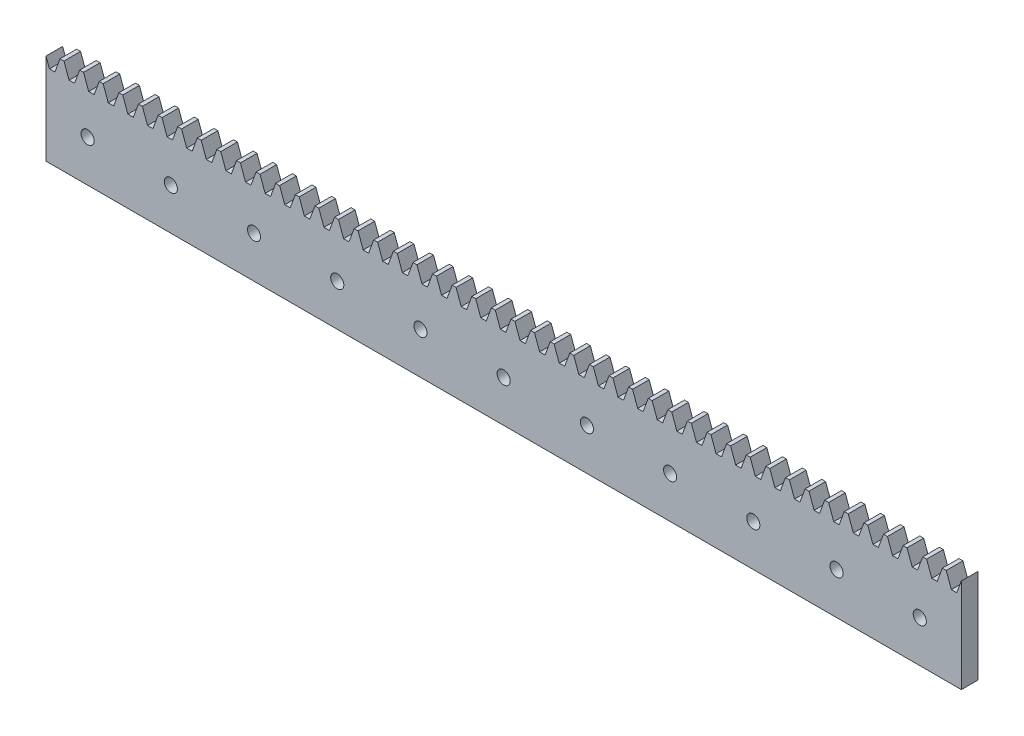
SolidWorks part; units mm, degrees
extrude "Blank" add sketch "BlankSke" against normal blind 4
sketch "BlankSke" plane through (0, 0, 0) normal (0, 0, 1) x (1, 0, 0)
  line L1 (0, 0) -> (660, 0)
  line L2 (0, 0) -> (0, 23)
  line L3 (0, 23) -> (660, 23)
  line L4 (660, 0) -> (660, 23)
  dimension "Length" = 660
  dimension "Blank_height" = 23
ref_plane "Plane1" through (0, 0, 0) normal (0, 0, 1) x (1, 0, 0)
ref_plane "Plane2" through (0, 0, 0) normal (0, 1, 0) x (1, 0, 0)
ref_plane "Plane3" through (0, 0, 0) normal (1, 0, 0) x (0, 0, -1)
other "Configuration Table"
sketch "HoldingSke" plane through (0, 0, 0) normal (0, 1, 0) x (1, 0, 0)
  line L0 (0, 0) -> (0.0928, 0.6602)
  line L1 (-15, 0) -> (100, 0) construction
  line L2 (0, 0) -> (-2.1039, 2.3779)
  line L3 (0, 0) -> (-11.863, 4.5341)
  line L4 (0, 0) -> (-6.8053, 5.3169)
  line L5 (0, 0) -> (-23.7986, -8.8762)
  line L6 (0, 0) -> (-10.5278, -7.1032)
  line L9 (-71.009, 38.7566) -> (549.1882, 264.4899)
  line L10 (-76.2, 3.8779) -> (-54.7, 3.8779)
  line L11 (0, 0) -> (-4, 0)
  line L12 (-76.2, 101.6) -> (-76.147, 101.6)
  line L13 (24.9733, 27.94) -> (52.9518, 28.4284)
  line L14 (24.9733, 27.94) -> (24.9743, 27.94)
  line L15 (24.9733, 27.94) -> (100.4006, 29.5858)
  circle A0 centre (0, 0) radius 19.05
  circle A1 centre (0, 0) radius 10.75
  circle A2 centre (0, 0) radius 12.7
  dimension "MPH" = 21.5
  dimension "Diameter" = 38.1
  dimension "Num_teeth" = 142
  dimension "Pitch" = 0.6667
  dimension "Show_teeth" = 998
  dimension "Thickness" = 12.7
  dimension "Ap" = 20
  dimension "Pitch_height" = 21.5
  dimension "Width" = 4
  dimension "Backlash" = 0.053
  dimension "Addendum_fac" = 1
  dimension "Dedendum_fac" = 1.25
  dimension "Clearance_fac" = 0.25
  dimension "Dedendum_add" = 0.001
  dimension "Length" = 660
  dimension "Module" = 1.5
sketch "TooCutSkeIll" plane through (0, 0, 0) normal (0, 0, 1) x (1, 0, 0)
  line L0 (-1.8687, 22.9605) -> (-0.7447, 19.8724)
  line L1 (-0.3914, 19.625) -> (0.3914, 19.625)
  line L2 (0.7447, 19.8724) -> (1.8687, 22.9605)
  line L3 (660, 23) -> (0, 23) construction
  line L4 (0, 0) -> (0, 64.897) construction
  line L5 (-13.208, 21.5) -> (12.954, 21.5) construction
  line L6 (0, 0) -> (660, 0) construction
  line L7 (1.3371, 21.5) -> (1.3371, 48.7463) construction
  line L8 (-1.3371, 21.5) -> (-1.3371, 48.7463) construction
  line L9 (1.9251, 23) -> (1.9251, 23.0254)
  line L10 (-1.9251, 23) -> (-1.9251, 23.0254)
  line L11 (-1.9251, 23.0254) -> (1.9251, 23.0254)
  arc A0 (0.3914, 19.625) -> (0.7447, 19.8724) centre (0.3914, 20.001) ccw
  arc A1 (-0.7447, 19.8724) -> (-0.3914, 19.625) centre (-0.3914, 20.001) ccw
  arc A2 (1.9251, 23) -> (1.8687, 22.9605) centre (1.9251, 22.94) ccw
  arc A3 (-1.8687, 22.9605) -> (-1.9251, 23) centre (-1.9251, 22.94) ccw
  dimension "Pitch_height" = 21.5
  dimension "Addendum_plus" = 1.5254
  dimension "Pressure_angle" = 20
  dimension "Gap_width" = 2.6742
  dimension "Dedendum" = 1.875
extrude "ToothCutIll" [suppressed] cut sketch "TooCutSkeIll" against normal through all
sketch "TooCutSkeSim" plane through (0, 0, 0) normal (0, 0, 1) x (1, 0, 0)
  line L0 (0.6547, 19.625) -> (-0.6547, 19.625)
  line L1 (1.8923, 23.0254) -> (0.6547, 19.625)
  line L2 (0, 17.4625) -> (0, 53.467) construction
  line L3 (1.8923, 23.0254) -> (-1.8923, 23.0254)
  line L6 (-1.8923, 23.0254) -> (-0.6547, 19.625)
  line L9 (-1.3371, 21.5) -> (1.3371, 21.5) construction
  line L10 (0, 0) -> (660, 0) construction
  line L11 (1.3371, 21.5) -> (1.3371, 53.467) construction
  line L12 (-1.3371, 21.5) -> (-1.3371, 53.467) construction
  dimension "Pitch_height" = 21.5
  dimension "Addendum_plus" = 1.5254
  dimension "Pressure_angle" = 20
  dimension "Gap_width" = 2.6742
  dimension "Dedendum" = 1.875
extrude "ToothCutSim" cut sketch "TooCutSkeSim" against normal through all
pattern_linear "TeethCuts" count 141 spacing 4.7124 along (1, 0, 0) of "ToothCutIll", "ToothCutSim"
sketch "草图2" plane through (0, 0, 0) normal (0, 0, 1) x (1, 0, 0)
  line L0 (660, 0) -> (660, 19.625) construction
  line L2 (0, 0) -> (660, 0) construction
  circle A0 centre (650, 10) radius 1.575
  circle A1 centre (630, 10) radius 1.575
  circle A2 centre (610, 10) radius 1.575
  circle A3 centre (590, 10) radius 1.575
  circle A4 centre (570, 10) radius 1.575
  circle A5 centre (550, 10) radius 1.575
  circle A6 centre (530, 10) radius 1.575
  circle A7 centre (510, 10) radius 1.575
  circle A8 centre (490, 10) radius 1.575
  circle A9 centre (470, 10) radius 1.575
  circle A10 centre (450, 10) radius 1.575
  circle A11 centre (430, 10) radius 1.575
  circle A12 centre (410, 10) radius 1.575
  circle A13 centre (390, 10) radius 1.575
  circle A14 centre (370, 10) radius 1.575
  circle A15 centre (350, 10) radius 1.575
  circle A16 centre (330, 10) radius 1.575
  circle A17 centre (310, 10) radius 1.575
  circle A18 centre (290, 10) radius 1.575
  circle A19 centre (270, 10) radius 1.575
  circle A20 centre (250, 10) radius 1.575
  circle A21 centre (230, 10) radius 1.575
  circle A22 centre (210, 10) radius 1.575
  circle A23 centre (190, 10) radius 1.575
  circle A24 centre (170, 10) radius 1.575
  circle A25 centre (150, 10) radius 1.575
  circle A26 centre (130, 10) radius 1.575
  circle A27 centre (110, 10) radius 1.575
  circle A28 centre (90, 10) radius 1.575
  circle A29 centre (70, 10) radius 1.575
  circle A30 centre (50, 10) radius 1.575
  circle A31 centre (30, 10) radius 1.575
  circle A32 centre (10, 10) radius 1.575
  dimension "D4" = 3.15
  dimension "D1" = 10
  dimension "D3" = 20
  dimension "D5" = 10
  dimension "D2" = 33
extrude "切除-拉伸2" cut sketch "草图2" against normal through all
sketch "草图3" plane through (0, 0, 0) normal (0, 0, 1) x (1, 0, 0)
  line L1 (0, 0) -> (220, 0)
  line L2 (0, 0) -> (0, 92.025)
  line L3 (0, 92.025) -> (220, 92.025)
  line L4 (220, 0) -> (220, 92.025)
  line L5 (660, 0) -> (440, 0)
  line L6 (660, 0) -> (660, 80.4663)
  line L7 (660, 80.4663) -> (440, 80.4663)
  line L8 (440, 0) -> (440, 80.4663)
  dimension "D1" = 220
  dimension "D2" = 220
extrude "切除-拉伸3" cut sketch "草图3" against normal through all
equation "' \"Module@HoldingSke\" = 6.35"
equation "' \"Num_teeth@HoldingSke\" = 12"
equation "' \"Ap@HoldingSke\" =  20"
equation "' \"Ap@HoldingSke\" = 20"
equation "' \"Width@HoldingSke\" = 0.25 * 25.4"
equation "' \"Show_teeth@HoldingSke\" = 500"
equation "' \"Backlash@HoldingSke\" = 0.009 * 25.4"
equation "' \"Addendum_fac@HoldingSke\" = 1.0"
equation "' \"Dedendum_fac@HoldingSke\" = 1.25"
equation "' \"Dedendum_add@HoldingSke\" = 0.00005 * 25.4"
equation "' \"Clearance_fac@HoldingSke\" = 0.25"
equation "' \"Pitch_height@HoldingSke\" = 1 * 25.4"
equation "' \"Length@HoldingSke\" = 4.71 * 25.4"
equation "\"Pitch@HoldingSke\" = 1 / \"Module@HoldingSke\""
equation "\"MPH@HoldingSke\" = \"Dedendum_fac@HoldingSke\" / \"Pitch@HoldingSke\" + 2 * \"Dedendum_add@HoldingSke\" + 0.002 * 25.4"
equation "\"MPH@HoldingSke\" = ((sgn( \"MPH@HoldingSke\" - \"Pitch_height@HoldingSke\")+1)*( \"MPH@HoldingSke\" - \"Pitch_height@HoldingSke\"))/2 + \"Pitch_height@HoldingSke\""
equation "\"Blank_height@BlankSke\" = \"Pitch_height@HoldingSke\" + \"Addendum_fac@HoldingSke\"  / \"Pitch@HoldingSke\" "
equation "\"Length@BlankSke\" =  \"Length@HoldingSke\""
equation "\"Face_width@Blank\" = \"Width@HoldingSke\""
equation "\"Pressure_angle@TooCutSkeIll\" = \"Ap@HoldingSke\""
equation "\"Addendum_plus@TooCutSkeIll\" =  \"Addendum_fac@HoldingSke\"  / \"Pitch@HoldingSke\" + 0.001 *25.4"
equation "\"Dedendum@TooCutSkeIll\" = \"Dedendum_fac@HoldingSke\"  / \"Pitch@HoldingSke\""
equation "\"Pitch_height@TooCutSkeIll\" =  \"MPH@HoldingSke\""
equation "\"Gap_width@TooCutSkeIll\" = 3.14159265 / 2 / \"Pitch@HoldingSke\" + 6 * \"Backlash@HoldingSke\""
equation "\"Pressure_angle@TooCutSkeSim\" = \"Ap@HoldingSke\""
equation "\"Addendum_plus@TooCutSkeSim\" =  \"Addendum_fac@HoldingSke\"  / \"Pitch@HoldingSke\" + 0.001 * 25.4"
equation "\"Dedendum@TooCutSkeSim\" = \"Dedendum_fac@HoldingSke\"  / \"Pitch@HoldingSke\""
equation "\"Pitch_height@TooCutSkeSim\" =  \"MPH@HoldingSke\""
equation "\"Gap_width@TooCutSkeSim\" = 3.14159265 / 2 / \"Pitch@HoldingSke\" + 6 * \"Backlash@HoldingSke\""
equation "\"Root_fillet@TooCutSkeIll\" = \"Clearance_fac@HoldingSke\" / \"Pitch@HoldingSke\" + \"Dedendum_add@HoldingSke\""
equation "\"Break_rad@TooCutSkeIll\" = 0.02 / \"Pitch@HoldingSke\" * 2"
equation "\"Linear_pitch@TeethCuts\" = 3.14159265 / \"Pitch@HoldingSke\""
equation "\"Num_teeth@HoldingSke\" = int( ( \"Length@HoldingSke\" + 0 ) / (3.14159265 / \"Pitch@HoldingSke\")) + 0.9999  + 1"
equation " \"Num_teeth@TeethCuts\" = int( \"Show_teeth@HoldingSke\" ) + 1"
equation " \"Num_teeth@TeethCuts\" = ((sgn( \"Num_teeth@TeethCuts\" - \"Num_teeth@HoldingSke\" )-1)*( \"Num_teeth@TeethCuts\" - \"Num_teeth@HoldingSke\" ))/-2+ \"Num_teeth@HoldingSke\""
equation " \"Num_teeth@TeethCuts\" = ((sgn( \"Num_teeth@TeethCuts\" - 2.0)+1)*( \"Num_teeth@TeethCuts\" - 2.0))/2 +2.0"
